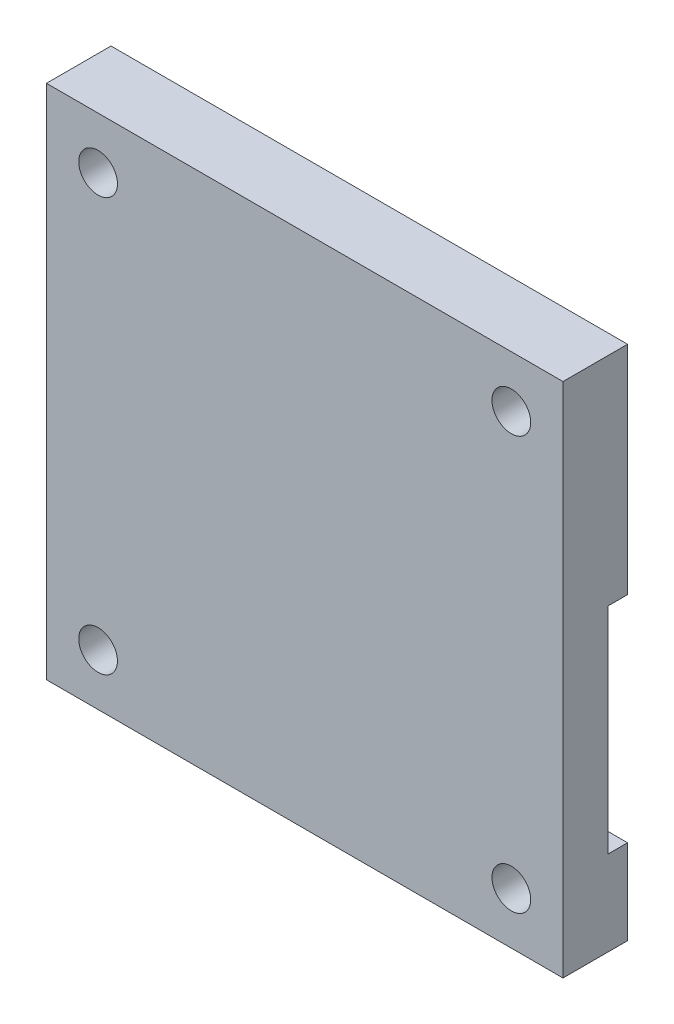
SolidWorks part; units mm, degrees
ref_plane "Front" through (0, 0, 0) normal (0, 0, 1) x (1, 0, 0)
ref_plane "Top" through (0, 0, 0) normal (0, 1, 0) x (1, 0, 0)
ref_plane "Right" through (0, 0, 0) normal (1, 0, 0) x (0, 0, -1)
sketch "Sketch1" plane through (0, 0, 0) normal (0, 0, 1) x (1, 0, 0)
  line L0 (0, 0) -> (20, 0) construction
  line L1 (20, -20) -> (-20, -20)
  line L2 (20, -20) -> (20, 20)
  line L3 (20, 20) -> (-20, 20)
  line L4 (-20, -20) -> (-20, 20)
  line L5 (20, -20) -> (-20, 20) construction
  line L6 (20, 20) -> (-20, -20) construction
  line L8 (-16, 16) -> (16, 16) construction
  line L9 (-16, 16) -> (-16, -16) construction
  line L10 (-16, -16) -> (16, -16) construction
  line L11 (16, 16) -> (16, -16) construction
  line L12 (0, -16) -> (0, 16) construction
  line L13 (-16, 0) -> (16, 0) construction
  circle A0 centre (-16, 16) radius 1.5
  circle A1 centre (16, 16) radius 1.5
  circle A2 centre (-16, -16) radius 1.5
  circle A3 centre (16, -16) radius 1.5
  point P0 (0, 0)
  point P474 (0, 0)
  dimension "D3" = 3
  dimension "D4" = 3
  dimension "D7" = 3
  dimension "D8" = 3
  dimension "D1" = 40
  dimension "D2" = 40
  dimension "D5" = 32
  dimension "D6" = 32
extrude "Boss-Extrude1" add sketch "Sketch1" along normal blind 5
sketch "Sketch3" plane through (0, 0, 0) normal (0, 0, -1) x (-1, 0, 0)
  line L0 (-20, -20) -> (-20, 20) construction
  line L1 (-20, -13.43) -> (20, -13.43)
  line L2 (-20, -13.43) -> (-20, 3.2061)
  line L3 (-20, 3.2061) -> (20, 3.2061)
  line L4 (20, -13.43) -> (20, 3.2061)
  line L5 (0, 3.2061) -> (0, -13.43) construction
  line L6 (-20, -5.112) -> (20, -5.112) construction
  line L7 (20, 20) -> (20, -20) construction
  point P192 (0, -5.112)
extrude "Cut-Extrude1" cut sketch "Sketch3" against normal blind 1.5
